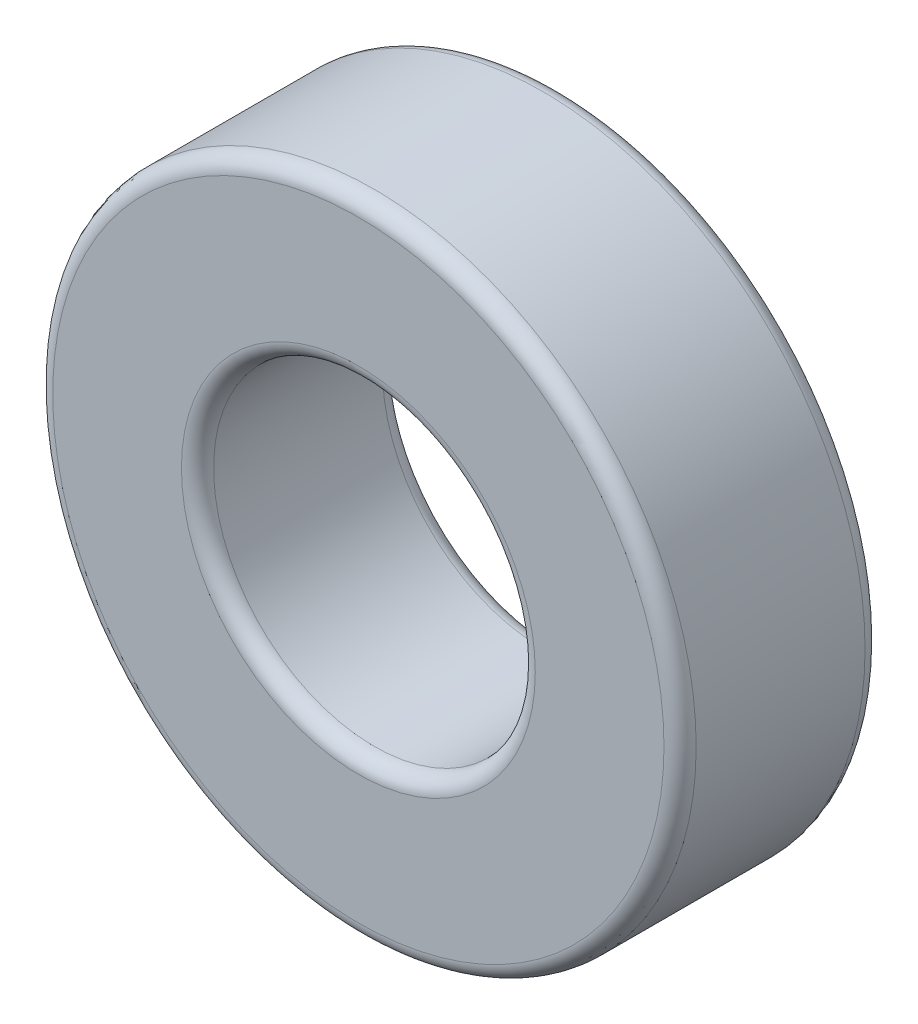
SolidWorks part; units mm, degrees
ref_plane "Face" through (0, 0, 0) normal (0, 0, 1) x (1, 0, 0)
ref_plane "Dessus" through (0, 0, 0) normal (0, 1, 0) x (1, 0, 0)
ref_plane "Droite" through (0, 0, 0) normal (1, 0, 0) x (0, 0, -1)
sketch "Esquisse1" plane through (0, 0, 0) normal (0, 0, 1) x (1, 0, 0)
  circle A0 centre (0, 0) radius 4
  circle A1 centre (0, 0) radius 2
  dimension "D1" = 4
  dimension "D2" = 8
extrude "Extrusion1" add sketch "Esquisse1" along normal blind 2.5
fillet "Congé1" radius 0.2
